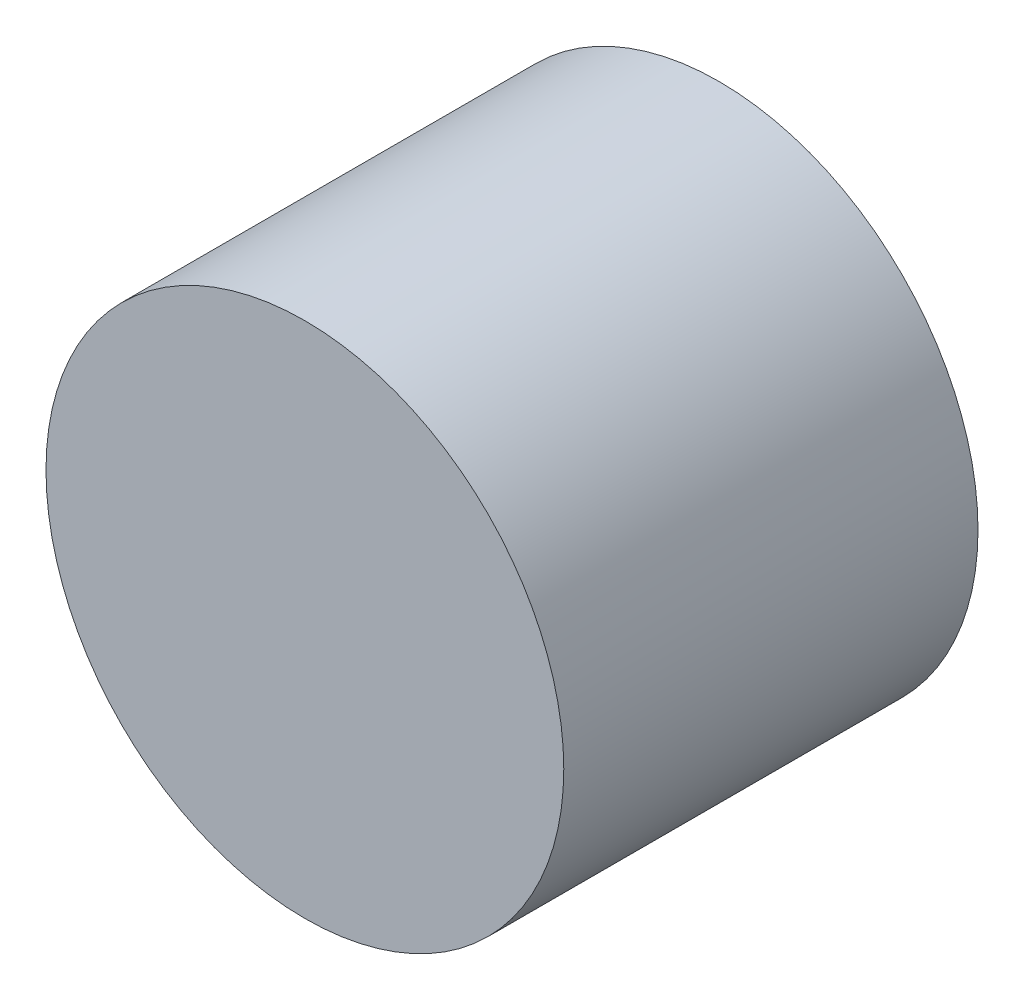
SolidWorks part; units mm, degrees
ref_plane "Front Plane" through (0, 0, 0) normal (0, 0, 1) x (1, 0, 0)
ref_plane "Top Plane" through (0, 0, 0) normal (0, 1, 0) x (1, 0, 0)
ref_plane "Right Plane" through (0, 0, 0) normal (1, 0, 0) x (0, 0, -1)
sketch "Sketch1" plane through (0, 0, 0) normal (0, 0, 1) x (1, 0, 0)
  circle A0 centre (0, 0) radius 2.5
  dimension "D1" = 5
extrude "Boss-Extrude1" add sketch "Sketch1" along normal blind 4
